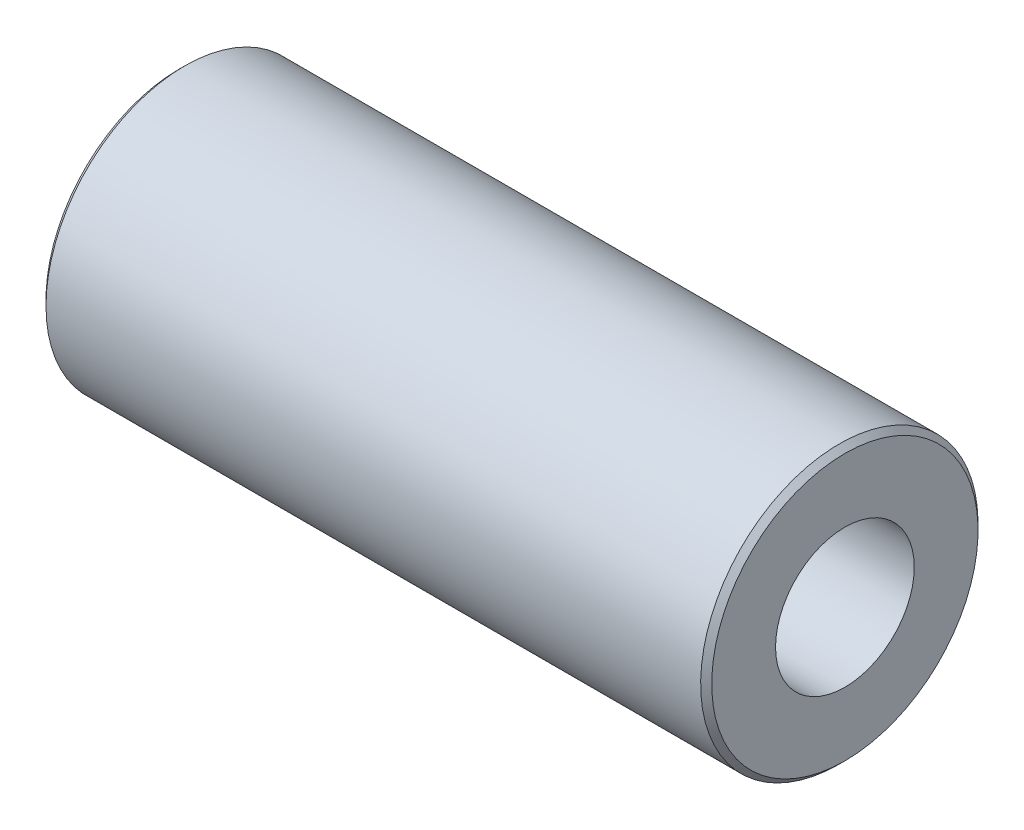
SolidWorks part; units mm, degrees
material "6061 合金"
ref_plane "前视基准面" through (0, 0, 0) normal (0, 0, 1) x (1, 0, 0)
ref_plane "上视基准面" through (0, 0, 0) normal (0, 1, 0) x (1, 0, 0)
ref_plane "右视基准面" through (0, 0, 0) normal (1, 0, 0) x (0, 0, -1)
sketch "草图1" plane through (0, 0, 0) normal (0, 0, 1) x (1, 0, 0)
  line L0 (-6, 0) -> (6, 0) construction
  line L1 (6, 0) -> (6, 2.5)
  line L2 (6, 2.5) -> (-6, 2.5)
  line L3 (-6, 2.5) -> (-6, 0)
  line L4 (6, 0) -> (-6, 0)
  point P4 (0, 0)
  dimension "D1" = 12
  dimension "D2" = 5
revolve "旋转1" add sketch "草图1" angle 360 about L0
hole_wizard "螺纹孔" positions "草图2" profile "草图3" tap size "M2" standard "GB"
sketch "草图2" plane through (-6, 0, 0) normal (-1, 0, 0) x (0, 0, 1)
  point P0 (0, 0)
sketch "草图3" plane through (-6, 0, 0) normal (0, 1, 0) x (0, 0, 1)
  line L0 (0, 0) -> (0, 10.7511)
  line L1 (0, 10.7511) -> (1.25, 10)
  line L2 (1.25, 10) -> (1.25, 0)
  line L5 (1.25, 0) -> (0, 0)
  line L10 (0, 10.7511) -> (-1.25, 10) construction
  line L11 (0, -6.35) -> (0, 107.95) construction
  dimension "螺纹孔钻头直径" = 2.5
  dimension "螺纹孔钻头深度" = 10
  dimension "导头角度" = 118
cosmetic thread "孔螺蚊线1" parameters "D1"=6, "D2"=2.9
mirror "镜向1" about plane through (0, 0, 0) normal (1, 0, 0) of "螺纹孔"
cosmetic thread "孔螺蚊线2" parameters "D1"=6, "D2"=2.9
chamfer "倒角1" distance 0.1 angle 45 2 edges at (6, -2.5, 0) (-6, -2.5, 0)
